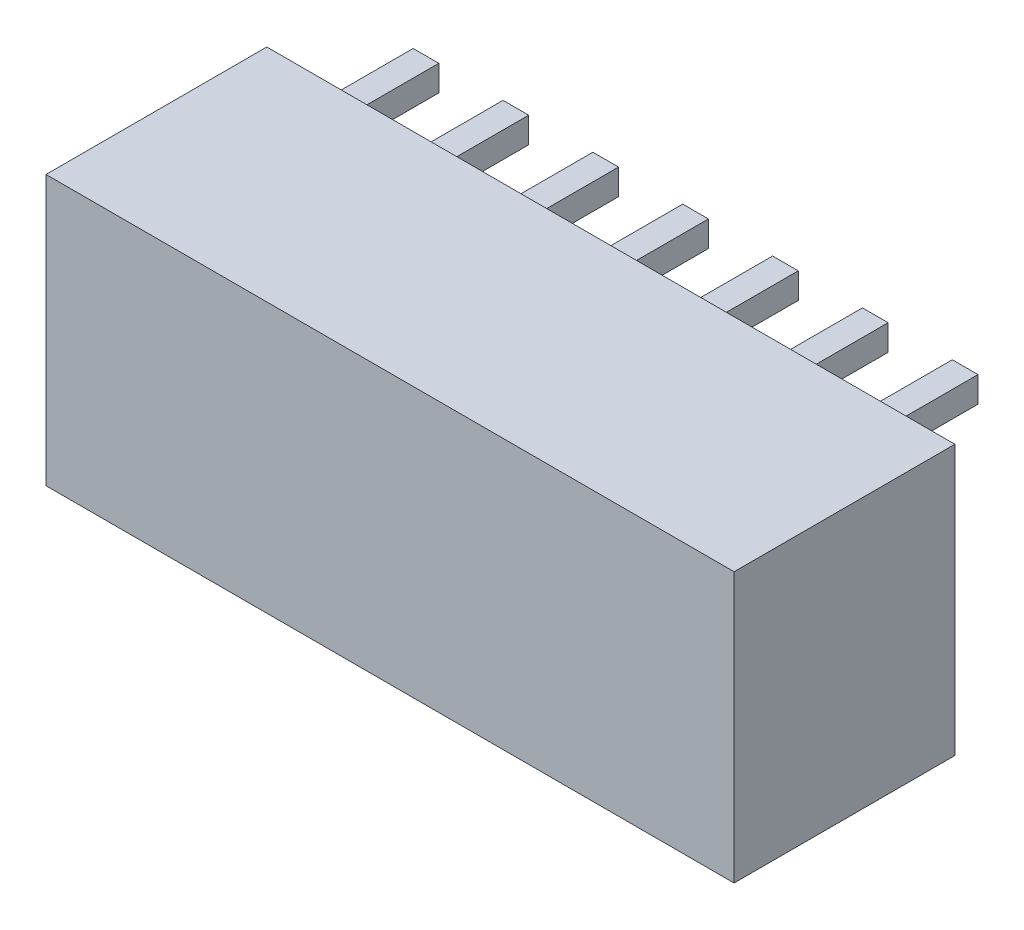
SolidWorks part; units mm, degrees
ref_plane "Спереди" through (0, 0, 0) normal (0, 0, 1) x (1, 0, 0)
ref_plane "Сверху" through (0, 0, 0) normal (0, 1, 0) x (1, 0, 0)
ref_plane "Справа" through (0, 0, 0) normal (1, 0, 0) x (0, 0, -1)
sketch "Эскиз1" plane through (0, 0, 0) normal (0, 0, 1) x (1, 0, 0)
  line L1 (-13.4, -5.25) -> (13.4, -5.25)
  line L2 (-13.4, -5.25) -> (-13.4, 5.25)
  line L3 (-13.4, 5.25) -> (13.4, 5.25)
  line L4 (13.4, -5.25) -> (13.4, 5.25)
  line L5 (-13.4, -5.25) -> (13.4, 5.25) construction
  line L6 (-13.4, 5.25) -> (13.4, -5.25) construction
  point P0 (0, 0)
  dimension "D1" = 26.8
  dimension "D2" = 10.5
extrude "Бобышка-Вытянуть1" add sketch "Эскиз1" along normal blind 8.6
sketch "Эскиз2" plane through (0, -5.25, 0) normal (0, -1, 0) x (1, 0, 0)
  line L0 (-12.4, 6.6) -> (12.4, 6.6)
  line L1 (12.4, 6.6) -> (12.4, 0.2)
  line L2 (12.4, 0.2) -> (10.2, 0.2)
  line L3 (10.2, 0.2) -> (10.2, 1.8)
  line L4 (10.2, 1.8) -> (-8.6, 1.8)
  line L5 (-8.6, 1.8) -> (-8.6, 0.2)
  line L6 (-8.6, 0.2) -> (-10.8, 0.2)
  line L7 (-12.4, 6.6) -> (-12.4, 1.8)
  line L8 (-12.4, 1.8) -> (-10.8, 1.8)
  line L9 (-10.8, 1.8) -> (-10.8, 0.2)
  line L10 (13.4, 8.6) -> (13.4, 0) construction
  line L11 (-13.4, 8.6) -> (-13.4, 0) construction
  line L12 (-13.4, 8.6) -> (13.4, 8.6) construction
  dimension "D1" = 4.8
  dimension "D2" = 6.4
  dimension "D3" = 2.2
  dimension "D4" = 2.2
  dimension "D5" = 3.2
  dimension "D6" = 4.8
  dimension "D7" = 1
  dimension "D8" = 2
extrude "Вырез-Вытянуть1" cut sketch "Эскиз2" against normal blind 7
sketch "Эскиз3" plane through (0, 0, 0) normal (0, 0, -1) x (-1, 0, 0)
  line L0 (13.4, -5.25) -> (-13.4, -5.25) construction
  line L1 (11, 4.75) -> (10, 4.75)
  line L2 (11, 4.75) -> (11, 3.75)
  line L3 (11, 3.75) -> (10, 3.75)
  line L4 (10, 4.75) -> (10, 3.75)
  line L5 (11, 4.75) -> (10, 3.75) construction
  line L6 (11, 3.75) -> (10, 4.75) construction
  line L7 (13.4, 5.25) -> (13.4, -5.25) construction
  point P0 (10.5, 4.25)
  dimension "D1" = 1
  dimension "D2" = 9.5
  dimension "D3" = 2.9
extrude "Бобышка-Вытянуть2" add sketch "Эскиз3" along normal blind 3.6 and the other way blind 5
chamfer "Фаска1" distance 0.3 distance2 0.3 4 edges at (-10, 4.25, -3.6) (-10.5, 3.75, -3.6) (-11, 4.25, -3.6) (-10.5, 4.75, -3.6)
pattern_linear "Линейный массив1" count 7 spacing 3.5 along (1, 0, 0) of "Бобышка-Вытянуть2", "Фаска1"
equation "\"N\"= 7"
equation "\"D1@Эскиз1\"= ( \"N\" - 1 ) * 3.5 + 5.8"
equation "\"D1@Линейный массив1\"=\"N\""
